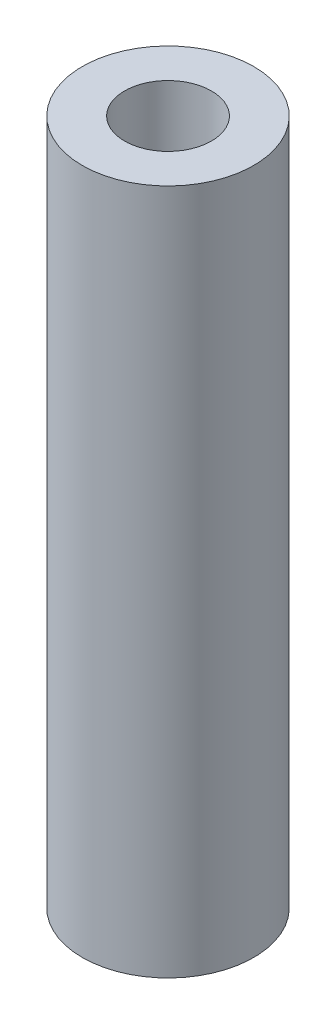
SolidWorks part; units mm, degrees
material "6061-T6 (SS)"
ref_plane "Front Plane" through (0, 0, 0) normal (0, 0, 1) x (1, 0, 0)
ref_plane "Top Plane" through (0, 0, 0) normal (0, 1, 0) x (1, 0, 0)
ref_plane "Right Plane" through (0, 0, 0) normal (1, 0, 0) x (0, 0, -1)
sketch "Sketch1" plane through (0, 0, 0) normal (0, 1, 0) x (1, 0, 0)
  circle A0 centre (0, 0) radius 2.413
  circle A1 centre (0, 0) radius 4.7625
  dimension "D1" = 4.826
  dimension "D2" = 9.525
extrude "Boss-Extrude1" add sketch "Sketch1" along normal blind 38.1
